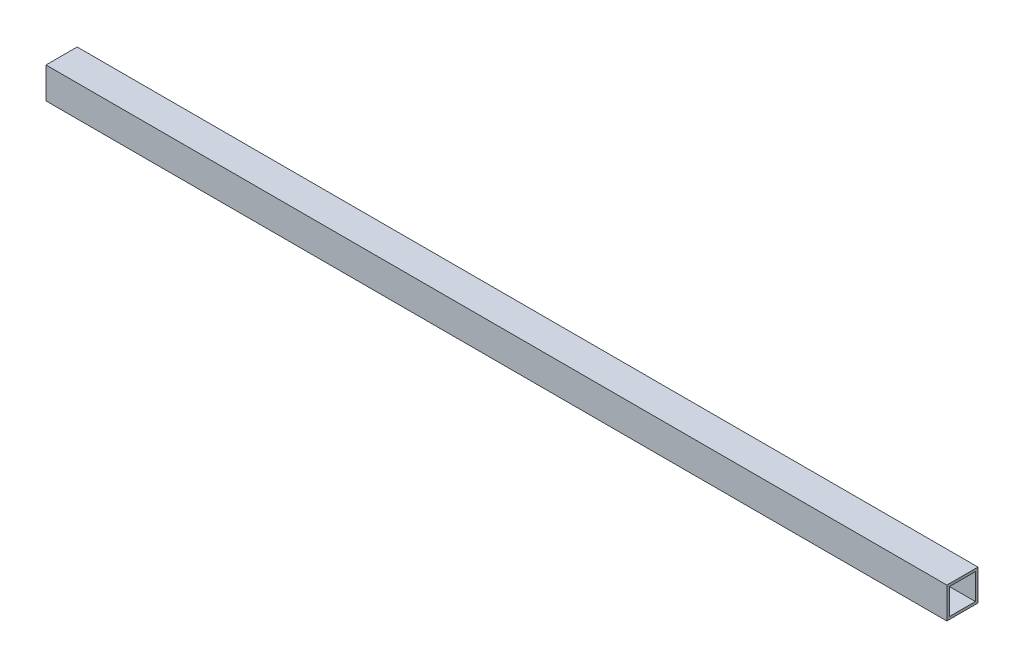
SolidWorks part; units mm, degrees
material "6061 Alloy"
ref_plane "Front Plane" through (0, 0, 0) normal (0, 0, 1) x (1, 0, 0)
ref_plane "Top Plane" through (0, 0, 0) normal (0, 1, 0) x (1, 0, 0)
ref_plane "Right Plane" through (0, 0, 0) normal (1, 0, 0) x (0, 0, -1)
sketch "Sketch1" plane through (0, 0, 0) normal (1, 0, 0) x (0, 0, -1)
  line L0 (3.175, 3.175) -> (34.925, 3.175)
  line L1 (0, 0) -> (38.1, 0)
  line L2 (0, 0) -> (0, 38.1)
  line L3 (0, 38.1) -> (38.1, 38.1)
  line L4 (38.1, 0) -> (38.1, 38.1)
  line L5 (34.925, 3.175) -> (34.925, 34.925)
  line L6 (3.175, 34.925) -> (34.925, 34.925)
  line L7 (3.175, 3.175) -> (3.175, 34.925)
  dimension "D2" = 38.1
  dimension "D3" = 38.1
  dimension "D1" = 3.175
extrude "Boss-Extrude1" add sketch "Sketch1" along normal blind 1101.725
hole_wizard "#10 (0.1935) Diameter Hole1" positions "Sketch2" profile "Sketch3" hole size "#10" standard "ANSI Inch"
sketch "Sketch2" plane through (0, 0, 0) normal (0, 1, 0) x (1, 0, 0)
  line L0 (0, 19.05) -> (1101.725, 19.05) construction
  line L1 (0, 38.1) -> (0, 0) construction
  line L2 (1101.725, 38.1) -> (1101.725, 0) construction
  point P0 (260.35, 19.05)
  point P2 (869.95, 19.05)
  dimension "D1" = 260.35
  dimension "D2" = 231.775
sketch "Sketch3" plane through (260.35, 0, -19.05) normal (1, 0, 0) x (0, 0, -1)
  line L0 (0, 0) -> (0, 3.175)
  line L1 (0, 3.175) -> (2.4574, 3.175)
  line L2 (2.4574, 3.175) -> (2.4574, 0)
  line L5 (2.4574, 0) -> (0, 0)
  line L11 (0, -6.35) -> (0, 107.95) construction
  dimension "Thru Hole Dia." = 4.9149
  dimension "Thru Hole Depth" = 3.175
